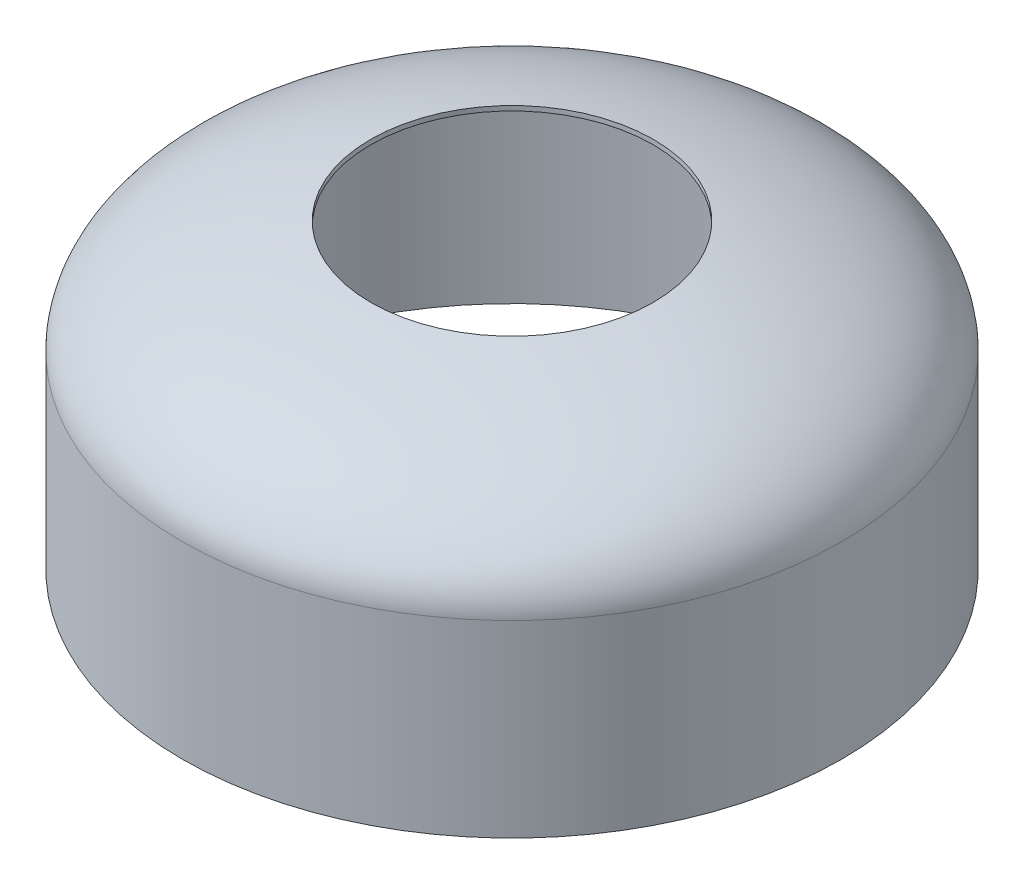
SolidWorks part; units mm, degrees
ref_plane "Front Plane" through (0, 0, 0) normal (0, 0, 1) x (1, 0, 0)
ref_plane "Top Plane" through (0, 0, 0) normal (0, 1, 0) x (1, 0, 0)
ref_plane "Right Plane" through (0, 0, 0) normal (1, 0, 0) x (0, 0, -1)
sketch "Sketch1" plane through (0, 0, 0) normal (0, 0, 1) x (1, 0, 0)
  line L0 (175.26, -101.6) -> (175.26, 0)
  line L1 (175.26, -101.6) -> (177.8, -101.6)
  line L2 (177.8, -101.6) -> (177.8, 0)
  line L3 (55.88, 0) -> (-55.88, 0) construction
  line L4 (76.2, 60.96) -> (76.2, 58.42)
  line L5 (0, -97.3311) -> (0, 97.3311) construction
  ellipse E0 centre (0, 0) end of major axis (177.8, 0) minor radius 67.4704 (177.8, 0) -> (76.2, 60.96) ccw
  ellipse E1 centre (0, 0) end of major axis (175.26, 0) minor radius 64.8725 (175.26, 0) -> (76.2, 58.42) ccw
  dimension "D1" = 177.8
  dimension "D2" = 2.54
  dimension "D3" = 101.6
  dimension "D4" = 2.54
  dimension "D5" = 76.2
  dimension "D6" = 58.42
ref_axis "Axis1" through (0, -109.728, 0) along (0, 1, 0)
revolve "Revolve1" add sketch "Sketch1" angle 360 about axis through (0, -109.728, 0) along (0, 1, 0)
